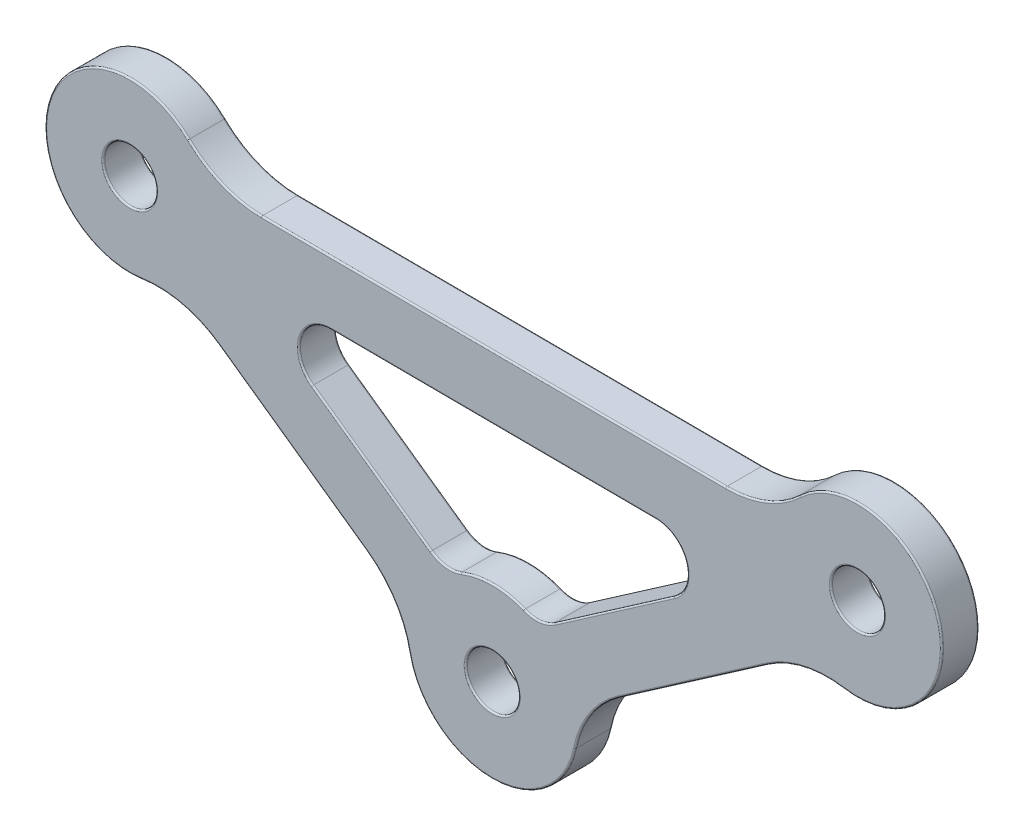
SolidWorks part; units mm, degrees
ref_plane "Front Plane" through (0, 0, 0) normal (0, 0, 1) x (1, 0, 0)
ref_plane "Top Plane" through (0, 0, 0) normal (0, 1, 0) x (1, 0, 0)
ref_plane "Right Plane" through (0, 0, 0) normal (1, 0, 0) x (0, 0, -1)
sketch "Sketch1" plane through (0, 0, 0) normal (0, 0, 1) x (1, 0, 0)
  line L0 (9.6755, 229.4213) -> (-59.1324, 229.7735) construction
  line L1 (9.6755, 229.4213) -> (-59.1324, 229.7735) construction
  line L2 (-59.1324, 229.7735) -> (-24.8517, 205.5075) construction
  line L3 (-59.1324, 229.7735) -> (-24.8517, 205.5075) construction
  line L4 (-24.8517, 205.5075) -> (9.6755, 229.4213) construction
  line L5 (-24.8517, 205.5075) -> (9.6755, 229.4213) construction
sketch "Sketch2" plane through (0, 0, 0) normal (0, 0, 1) x (1, 0, 0)
  circle A0 centre (-59.1324, 229.7735) radius 8
  circle A1 centre (-24.8517, 205.5075) radius 8
  circle A2 centre (9.6755, 229.4213) radius 8
  circle A3 centre (9.6755, 229.4213) radius 2.5
  circle A4 centre (-24.8517, 205.5075) radius 2.5
  circle A5 centre (-59.1324, 229.7735) radius 2.5
  dimension "D1" = 16
  dimension "D2" = 5
  dimension "D3" = 5
extrude "Boss-Extrude1" add sketch "Sketch2" against normal blind 3.5
sketch "Sketch4" plane through (0, 0, 0) normal (0, 0, 1) x (1, 0, 0)
  line L0 (-52.2284, 229.7381) -> (2.7716, 229.4567)
  line L1 (9.6755, 229.4213) -> (-59.1324, 229.7735) construction
  line L2 (4.743, 226.0051) -> (-19.9193, 208.9238)
  line L3 (-24.8517, 205.5075) -> (9.6755, 229.4213) construction
  line L4 (-54.2351, 226.3069) -> (-29.749, 208.9741)
  line L5 (-59.1324, 229.7735) -> (-24.8517, 205.5075) construction
  point P12 (-24.7284, 229.5974)
  point P13 (-7.5881, 217.4644)
  point P14 (-41.992, 217.6405)
  dimension "D1" = 55
  dimension "D2" = 30
extrude "Extrude-Thin1" add sketch "Sketch4" against normal blind 3.5 thin thin type mid plane wall 6
fillet "Fillet1" radius 3 4 edges at (-49.6331, 226.7248, -1.75) (0.1455, 226.4701, -1.75) (-20.4632, 212.1963, -1.75) (-29.1716, 212.2409, -1.75)
fillet "Fillet2" radius 10 6 edges at (-51.7009, 232.7355, -1.75) (2.2747, 232.4593, -1.75) (5.2869, 222.7325, -1.75) (-17.0469, 207.2639, -1.75) (-32.6381, 207.3437, -1.75) (-54.8125, 223.0401, -1.75)
fillet "Fillet3" radius 0.15 46 edges at (-22.3517, 205.5075, -3.5) (12.1755, 229.4213, -3.5) (-56.6324, 229.7735, -3.5) (-6.5188, 224.4063, -3.5) (-13.3285, 217.1379, 0) (-13.3285, 217.1379, -3.5) (-20.363, 212.7071, -3.5) (-24.8108, 213.5074, -3.5) (-29.2665, 212.7527, -3.5) (-36.2553, 217.2552, -3.5) (-36.2553, 217.2552, 0) (-42.9903, 224.5929, -3.5) (-24.7438, 226.5974, 0) (-24.7438, 226.5974, -3.5) (-34.1211, 207.5108, -3.5) (-24.8927, 197.5076, -3.5) (-15.5623, 207.4158, -3.5) (-5.88, 214.9982, -3.5) (-5.88, 214.9982, 0) (4.6227, 221.3962, -3.5) (17.3174, 231.7879, -3.5) (0.9715, 233.1863, -3.5) (-24.7131, 232.5974, -3.5) (-24.7131, 232.5974, 0) (-50.3903, 233.4492, -3.5) (-66.7497, 232.2181, -3.5) (-54.162, 221.697, -3.5) (-43.7253, 215.1919, -3.5) (-43.7253, 215.1919, 0) (-22.3517, 205.5075, 0) (12.1755, 229.4213, 0) (-56.6324, 229.7735, 0) (-29.2665, 212.7527, 0) (-24.8108, 213.5074, 0) (-20.363, 212.7071, 0) (-6.5188, 224.4063, 0) (-42.9903, 224.5929, 0) (0.9715, 233.1863, 0) (17.3174, 231.7879, 0) (4.6227, 221.3962, 0) (-15.5623, 207.4158, 0) (-24.8927, 197.5076, 0) (-34.1211, 207.5108, 0) (-54.162, 221.697, 0) (-66.7497, 232.2181, 0) (-50.3903, 233.4492, 0)
